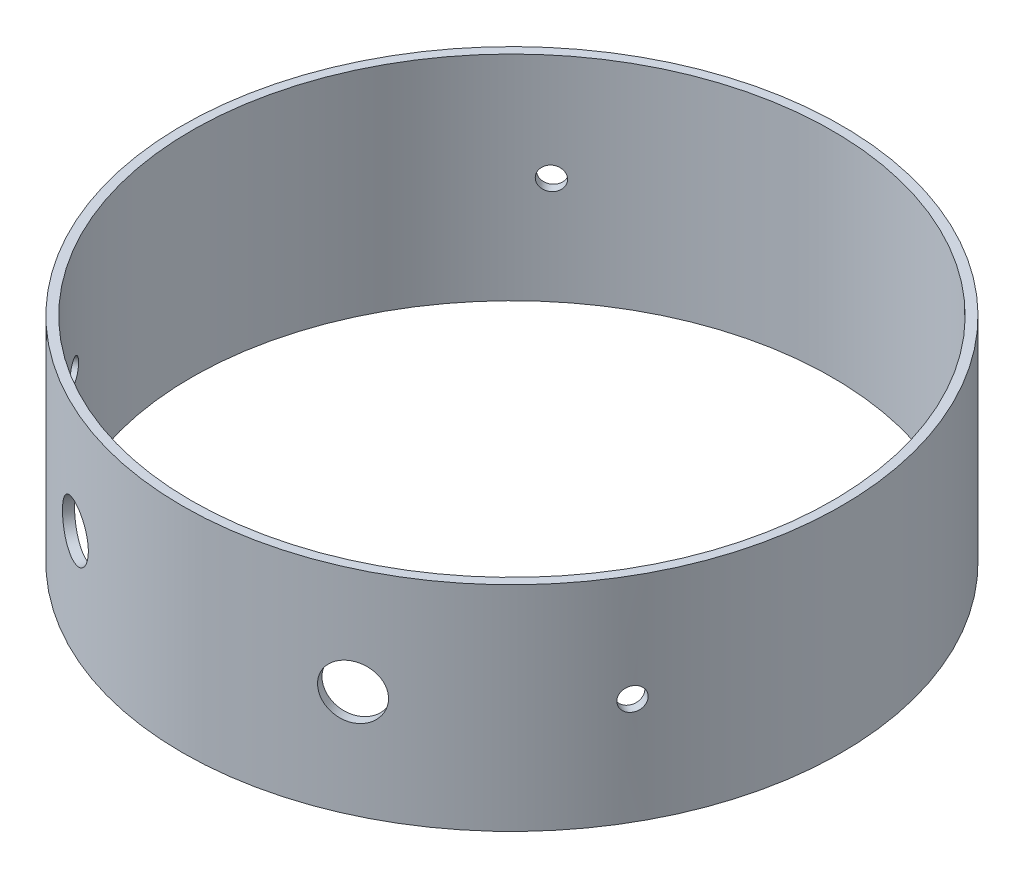
SolidWorks part; units mm, degrees
ref_plane "Front Plane" through (0, 0, 0) normal (0, 0, 1) x (1, 0, 0)
ref_plane "Top Plane" through (0, 0, 0) normal (0, 1, 0) x (1, 0, 0)
ref_plane "Right Plane" through (0, 0, 0) normal (1, 0, 0) x (0, 0, -1)
sketch "Sketch1" plane through (0, 0, 0) normal (0, 1, 0) x (1, 0, 0)
  circle A0 centre (0, 0) radius 76.2
  circle A1 centre (0, 0) radius 78.359
  dimension "D1" = 156.718
  dimension "D2" = 152.4
extrude "Boss-Extrude1" add sketch "Sketch1" along normal blind 50.8
ref_plane "Plane1" through (0, 0, 45.72) normal (0, 0, 1) x (1, 0, 0)
ref_plane "Plane2" through (-33.1159, 0, 71.0174) normal (-0.4226, 0, 0.9063) x (0, -1, 0)
ref_plane "Plane3" through (33.1159, 0, 71.0174) normal (0.4226, 0, 0.9063) x (0, -1, 0)
sketch "Sketch4" plane through (33.1159, 0, 71.0174) normal (0.4226, 0, 0.9063) x (0, -1, 0)
  circle A0 centre (-25.4, 0) radius 6.35
  dimension "D1" = 12.7
  dimension "D2" = 25.4
extrude "Cut-Extrude1" cut sketch "Sketch4" against normal blind 25.4
sketch "Sketch5" plane through (-33.1159, 0, 71.0174) normal (-0.4226, 0, 0.9063) x (0, -1, 0)
  circle A0 centre (-25.4, 0) radius 6.35
  dimension "D1" = 12.7
  dimension "D2" = 25.4
extrude "Cut-Extrude2" cut sketch "Sketch5" against normal blind 25.4
ref_plane "Plane4" through (67.8609, 0, 39.1795) normal (0.866, 0, 0.5) x (0, -1, 0)
sketch "Sketch6" plane through (67.8609, 0, 39.1795) normal (0.866, 0, 0.5) x (0, -1, 0)
  line L0 (0, -78.359) -> (0, 78.359) construction
  circle A0 centre (-25.4, 0) radius 2.7305
  dimension "D1" = 5.461
  dimension "D2" = 25.4
extrude "Cut-Extrude3" cut sketch "Sketch6" against normal blind 2.54
pattern_circular "CirPattern1" count 4 over 240 about axis through (0, 50.8, 0) along (0, -1, 0) of "Cut-Extrude3"
